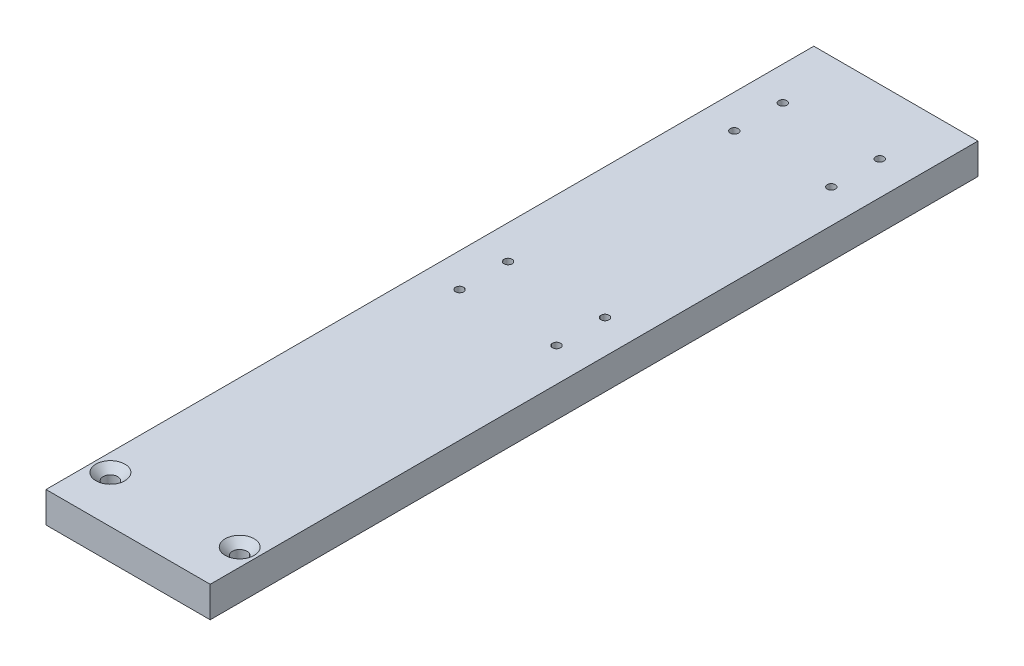
SolidWorks part; units mm, degrees
ref_plane "Front" through (0, 0, 0) normal (0, 0, 1) x (1, 0, 0)
ref_plane "Top" through (0, 0, 0) normal (0, 1, 0) x (1, 0, 0)
ref_plane "Right" through (0, 0, 0) normal (1, 0, 0) x (0, 0, -1)
sketch "Sketch1" plane through (0, 0, 0) normal (0, 0, 1) x (1, 0, 0)
  line L1 (-25.4, -4.7625) -> (25.4, -4.7625)
  line L2 (-25.4, -4.7625) -> (-25.4, 4.7625)
  line L3 (-25.4, 4.7625) -> (25.4, 4.7625)
  line L4 (25.4, -4.7625) -> (25.4, 4.7625)
  line L5 (-25.4, -4.7625) -> (25.4, 4.7625) construction
  line L6 (-25.4, 4.7625) -> (25.4, -4.7625) construction
  point P0 (0, 0)
  dimension "D1" = 50.8
  dimension "D2" = 9.525
extrude "Boss-Extrude1" add sketch "Sketch1" along normal mid plane 237.55
sketch "Sketch2" plane through (0, 4.7625, 0) normal (0, 1, 0) x (1, 0, 0)
  line L0 (25.4, 118.775) -> (-25.4, 118.775) construction
  line L1 (-20, 103.775) -> (20, 103.775)
  line L2 (-20, 103.775) -> (-20, -6.225)
  line L3 (-20, -6.225) -> (20, -6.225)
  line L4 (20, 103.775) -> (20, -6.225)
  point P6 (0, 103.775)
  dimension "D1" = 15
  dimension "D2" = 40
  dimension "D3" = 110
hole_wizard "Tap Drill for M3x0.5 Tap1" positions "Sketch3" profile "Sketch5" hole size "M3x0.5" standard "ANSI Metric" end condition through all
sketch "Sketch3" plane through (0, 4.7625, 0) normal (0, 1, 0) x (1, 0, 0)
  line L0 (-20, 103.775) -> (-20, -6.225) construction
  line L1 (20, 103.775) -> (20, -6.225) construction
  line L2 (-20, 103.775) -> (20, 103.775) construction
  line L3 (-20, 48.775) -> (20, 48.775)
  point P0 (-15, 98.775)
  point P2 (15, 98.775)
  point P4 (-15, 83.775)
  point P6 (15, 83.775)
  point P19 (15, 13.775)
  point P20 (-15, 13.775)
  point P21 (15, -1.225)
  point P22 (-15, -1.225)
  dimension "D1" = 5
  dimension "D2" = 5
  dimension "D3" = 5
  dimension "D4" = 15
sketch "Sketch5" plane through (-15, 4.7625, -98.775) normal (1, 0, 0) x (0, 0, 1)
  line L0 (0, 0) -> (0, 9.525)
  line L1 (0, 9.525) -> (1.25, 9.525)
  line L2 (1.25, 9.525) -> (1.25, 0)
  line L5 (1.25, 0) -> (0, 0)
  line L11 (0, -6.35) -> (0, 107.95) construction
  dimension "Thru Hole Dia." = 2.5
  dimension "Thru Hole Depth" = 9.525
hole_wizard "CSK for M4 SFHCS1" positions "Sketch8" profile "Sketch9" countersink size "M4" standard "ANSI Metric" end condition through all
sketch "Sketch8" plane through (0, 4.7625, 0) normal (0, 1, 0) x (1, 0, 0)
  line L0 (-20, -104.25) -> (20, -104.25)
  line L2 (25.4, -118.775) -> (-25.4, -118.775) construction
  point P0 (-20, -104.25)
  point P2 (20, -104.25)
  point P9 (0, -104.25)
  dimension "D1" = 14.525
  dimension "D2" = 40
sketch "Sketch9" plane through (-20, 4.7625, 104.25) normal (1, 0, 0) x (0, 0, 1)
  line L0 (0, 0) -> (0, 9.525)
  line L1 (0, 9.525) -> (2.25, 9.525)
  line L2 (2.25, 9.525) -> (2.25, 2.23)
  line L3 (2.25, 2.23) -> (4.48, 0)
  line L5 (4.48, 0) -> (0, 0)
  line L6 (-2.25, 2.23) -> (-4.48, 0) construction
  line L11 (0, -6.35) -> (0, 107.95) construction
  dimension "Thru Hole Dia." = 4.5
  dimension "Thru Hole Depth" = 9.525
  dimension "Near C'Sink Dia." = 8.96
  dimension "Near C'Sink Angle" = 90
equation "\"D1@Boss-Extrude1\"=150MM + 63.5MM +19.05 + 5mm"
